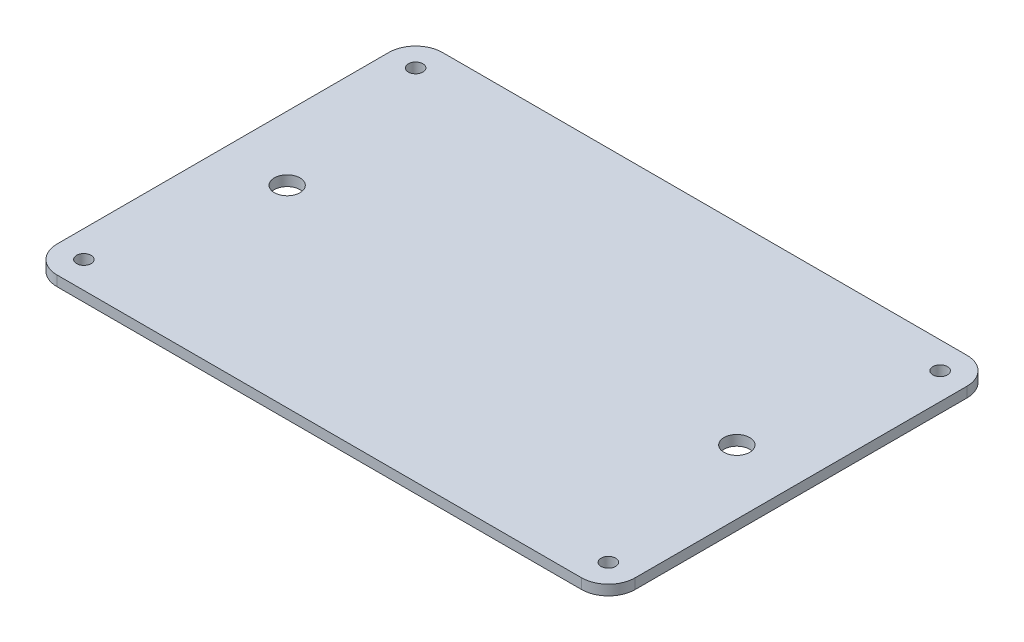
SolidWorks part; units mm, degrees
material "Plain Carbon Steel"
ref_plane "Front" through (0, 0, 0) normal (0, 0, 1) x (1, 0, 0)
ref_plane "Top" through (0, 0, 0) normal (0, 1, 0) x (1, 0, 0)
ref_plane "Right" through (0, 0, 0) normal (1, 0, 0) x (0, 0, -1)
sketch "Sketch1" plane through (0, 0, 0) normal (0, 1, 0) x (1, 0, 0)
  line L0 (-45, 0) -> (45, 0) construction
  line L1 (-45, 30) -> (45, 30) construction
  line L2 (-45, 30) -> (-45, -30) construction
  line L3 (-45, -30) -> (45, -30) construction
  line L4 (45, 30) -> (45, -30) construction
  line L5 (0, -30) -> (0, 30) construction
  line L6 (41.825, 26.825) -> (41.825, -26.825) construction
  line L7 (-41.825, -26.825) -> (41.825, -26.825) construction
  line L8 (-41.825, 26.825) -> (-41.825, -26.825) construction
  line L9 (-41.825, 26.825) -> (41.825, 26.825) construction
  line L10 (40.825, 25.825) -> (40.825, -25.825) construction
  line L11 (-40.825, -25.825) -> (40.825, -25.825) construction
  line L12 (-40.825, 25.825) -> (-40.825, -25.825) construction
  line L13 (-40.825, 25.825) -> (40.825, 25.825) construction
  line L14 (40.825, 21.65) -> (45, 21.65) construction
  line L15 (40.825, -21.65) -> (45, -21.65) construction
  line L16 (36.65, -25.825) -> (36.65, -30) construction
  line L17 (-36.65, -25.825) -> (-36.65, -30) construction
  line L18 (-40.825, -21.65) -> (-45, -21.65) construction
  line L19 (-36.65, 25.825) -> (-36.65, 30) construction
  line L20 (-40.825, 21.65) -> (-45, 21.65) construction
  line L21 (36.65, 25.825) -> (36.65, 30) construction
  line L22 (40.825, -25.825) -> (41.825, -25.825) construction
  circle A0 centre (-40.825, -25.825) radius 1 construction
  circle A1 centre (40.825, -25.825) radius 1 construction
  circle A2 centre (40.825, 25.825) radius 1 construction
  circle A3 centre (-40.825, 25.825) radius 1 construction
  circle A4 centre (40.825, -25.825) radius 4.175 construction
  circle A5 centre (40.825, 25.825) radius 4.175 construction
  circle A6 centre (-40.825, 25.825) radius 4.175 construction
  circle A7 centre (-40.825, -25.825) radius 4.175 construction
  dimension "D1" = 90
  dimension "D2" = 60
  dimension "D4" = 1
  dimension "D3" = 3.175
sketch "Sketch2" plane through (0, 0, 0) normal (0, 1, 0) x (1, 0, 0)
  line L0 (-45, 30) -> (-45, -30) construction
  line L1 (-45, -30) -> (45, -30) construction
  line L2 (45, 30) -> (45, -30) construction
  line L3 (-45, 30) -> (45, 30) construction
  line L16 (-45, 25.825) -> (-45, -25.825)
  line L17 (-40.825, -30) -> (40.825, -30)
  line L18 (45, 25.825) -> (45, -25.825)
  line L19 (-40.825, 30) -> (40.825, 30)
  circle A0 centre (40.825, 25.825) radius 4.175 construction
  circle A2 centre (-40.825, 25.825) radius 4.175 construction
  arc A6 (45, 25.825) -> (40.825, 30) centre (40.825, 25.825) ccw
  circle A7 centre (40.825, 25.825) radius 1.1303
  arc A8 (-40.825, 30) -> (-45, 25.825) centre (-40.825, 25.825) ccw
  circle A9 centre (-40.825, 25.825) radius 1.1303
  circle A14 centre (-40.825, -25.825) radius 1.1303
  circle A15 centre (40.825, -25.825) radius 1.1303
  arc A17 (-45, -25.825) -> (-40.825, -30) centre (-40.825, -25.825) ccw
  arc A18 (40.825, -30) -> (45, -25.825) centre (40.825, -25.825) ccw
  dimension "D1" = 2.2606
  dimension "D2" = 2.2606
  dimension "D3" = 2.2606
  dimension "D4" = 2.2606
extrude "Boss-Extrude3" add sketch "Sketch2" along normal blind 1.59
sketch "Sketch3" plane through (0, 0, 0) normal (0, -1, 0) x (1, 0, 0)
  line L0 (-45, 0) -> (45, 0) construction
  line L1 (-35, 0) -> (-45, 0) construction
  line L2 (-35, 30) -> (-35, -30) construction
  line L3 (-45, 30) -> (45, 30) construction
  line L4 (-45, -30) -> (45, -30) construction
  line L5 (35, 0) -> (45, 0) construction
  line L6 (35, -30) -> (35, 30) construction
  circle A0 centre (-35, 0) radius 2
  circle A1 centre (35, 0) radius 2
  dimension "D1" = 10
  dimension "D2" = 10
extrude "Cut-Extrude1" cut sketch "Sketch3" against normal up to vertex (1.59 mm away)
